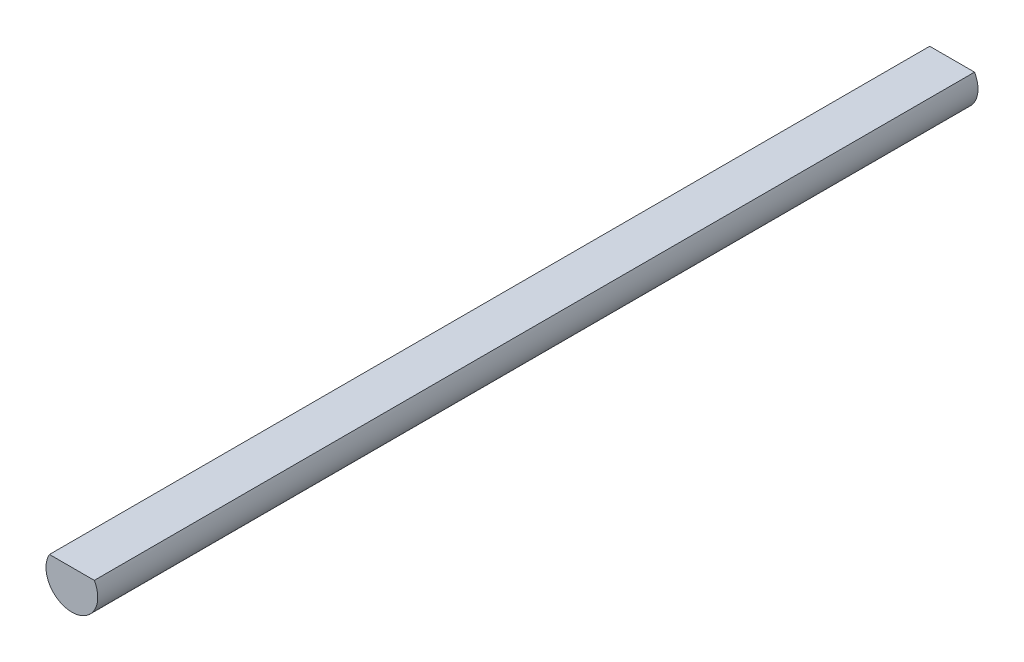
SolidWorks part; units mm, degrees
ref_plane "Front Plane" through (0, 0, 0) normal (0, 0, 1) x (1, 0, 0)
ref_plane "Top Plane" through (0, 0, 0) normal (0, 1, 0) x (1, 0, 0)
ref_plane "Right Plane" through (0, 0, 0) normal (1, 0, 0) x (0, 0, -1)
sketch "Sketch1" plane through (0, 0, 0) normal (0, 0, 1) x (1, 0, 0)
  line L0 (-5.4991, 3.1753) -> (5.4991, 3.1753)
  arc A0 (-5.4991, 3.1753) -> (5.4991, 3.1753) centre (0, 0) ccw
  dimension "D2" = 12.7
  dimension "D1" = 10.9982
extrude "Boss-Extrude1" add sketch "Sketch1" along normal blind 215.9 contours L0 A0
